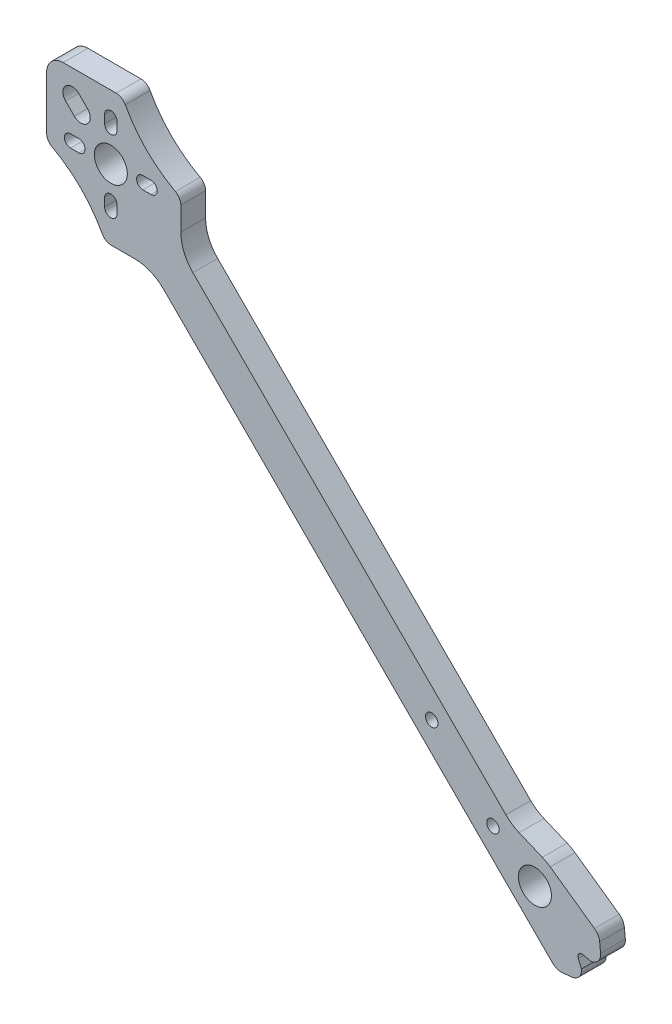
SolidWorks part; units mm, degrees
ref_plane "Alzado" through (0, 0, 0) normal (0, 0, 1) x (1, 0, 0)
ref_plane "Planta" through (0, 0, 0) normal (0, 1, 0) x (1, 0, 0)
ref_plane "Vista lateral" through (0, 0, 0) normal (1, 0, 0) x (0, 0, -1)
sketch "Croquis1" plane through (0, 0, 0) normal (0, 0, 1) x (1, 0, 0)
  line L0 (0, 0) -> (27.8544, 27.8544) construction
  line L1 (0, 0) -> (-42.4264, 42.4264) construction
  line L2 (0, 0) -> (0, 42.4264) construction
  line L3 (15.25, -15.25) -> (-15.25, -15.25) construction
  line L4 (15.25, -15.25) -> (15.25, 15.25) construction
  line L5 (15.25, 15.25) -> (-15.25, 15.25) construction
  line L6 (-15.25, -15.25) -> (-15.25, 15.25) construction
  line L7 (15.25, -15.25) -> (-15.25, 15.25) construction
  line L8 (15.25, 15.25) -> (-15.25, -15.25) construction
  line L9 (0, 42.4264) -> (-20, 42.4264) construction
  line L10 (-42.4264, 42.4264) -> (-38.8909, 45.9619) construction
  line L11 (-38.8909, 45.9619) -> (-31.0962, 38.1673) construction
  line L12 (-20, 42.7635) -> (-20, 80) construction
  line L13 (-42.4264, 42.4264) -> (-45.9619, 38.8909) construction
  line L14 (-45.9619, 38.8909) -> (-38.1673, 31.0962) construction
  line L15 (20, 42.7635) -> (20, 80) construction
  line L16 (38.8909, 45.9619) -> (31.0962, 38.1673) construction
  line L17 (42.4264, 42.4264) -> (38.8909, 45.9619) construction
  line L18 (42.4264, 42.4264) -> (45.9619, 38.8909) construction
  line L19 (-45.9619, -38.8909) -> (-38.1673, -31.0962) construction
  line L20 (0, 0) -> (-15.25, 0) construction
  line L21 (45.9619, 38.8909) -> (38.1673, 31.0962) construction
  line L22 (42.4264, -42.4264) -> (45.9619, -38.8909) construction
  line L23 (42.4264, -42.4264) -> (38.8909, -45.9619) construction
  line L24 (38.8909, -45.9619) -> (31.0962, -38.1673) construction
  line L25 (20, -42.7635) -> (20, -80) construction
  line L26 (-20, -42.7635) -> (-20, -80) construction
  line L27 (-38.8909, -45.9619) -> (-31.0962, -38.1673) construction
  line L28 (-42.4264, -42.4264) -> (-38.8909, -45.9619) construction
  line L29 (-42.4264, -42.4264) -> (-45.9619, -38.8909) construction
  line L30 (45.9619, -38.8909) -> (38.1673, -31.0962) construction
  line L31 (-20, 80) -> (20, 80) construction
  line L32 (0, 80) -> (0, 83) construction
  line L33 (-20, 80) -> (0, 83) construction
  line L34 (0, 83) -> (20, 80) construction
  line L35 (0, -80) -> (0, -83) construction
  line L36 (-20, -80) -> (20, -80) construction
  line L37 (0, -83) -> (20, -80) construction
  line L38 (-20, -80) -> (0, -83) construction
  line L39 (-11, -54) -> (-11, -67.5) construction
  line L41 (-15, -54) -> (-15, -67.5) construction
  line L43 (-13, -54) -> (-13, -67.5) construction
  line L44 (-9, -54) -> (-9, -67.5) construction
  line L45 (-7, -54) -> (-7, -67.5) construction
  line L46 (-5, -54) -> (-5, -67.5) construction
  line L47 (-3, -54) -> (-3, -67.5) construction
  line L48 (-1, -54) -> (-1, -67.5) construction
  line L49 (1, -54) -> (1, -67.5) construction
  line L50 (3, -54) -> (3, -67.5) construction
  line L51 (5, -54) -> (5, -67.5) construction
  line L52 (7, -54) -> (7, -67.5) construction
  line L53 (9, -54) -> (9, -67.5) construction
  line L54 (11, -54) -> (11, -67.5) construction
  line L55 (13, -54) -> (13, -67.5) construction
  line L56 (15, -54) -> (15, -67.5) construction
  line L57 (-11, -35) -> (-11, -48.5) construction
  line L58 (-9, -35) -> (-9, -48.5) construction
  line L59 (-7, -35) -> (-7, -48.5) construction
  line L60 (-5, -35) -> (-5, -48.5) construction
  line L61 (-3, -35) -> (-3, -48.5) construction
  line L62 (-1, -35) -> (-1, -48.5) construction
  line L63 (1, -35) -> (1, -48.5) construction
  line L64 (3, -35) -> (3, -48.5) construction
  line L65 (5, -35) -> (5, -48.5) construction
  line L66 (7, -35) -> (7, -48.5) construction
  line L67 (9, -35) -> (9, -48.5) construction
  line L68 (11, -35) -> (11, -48.5) construction
  line L69 (13, -35) -> (13, -48.5) construction
  line L70 (15, -35) -> (15, -48.5) construction
  line L71 (-15, -35) -> (-15, -48.5) construction
  line L72 (-13, -35) -> (-13, -48.5) construction
  line L73 (-15, 54) -> (-15, 67.5) construction
  line L74 (-13, 35) -> (-13, 48.5) construction
  line L75 (-15, 35) -> (-15, 48.5) construction
  line L76 (15, 35) -> (15, 48.5) construction
  line L77 (13, 35) -> (13, 48.5) construction
  line L78 (11, 35) -> (11, 48.5) construction
  line L79 (9, 35) -> (9, 48.5) construction
  line L80 (7, 35) -> (7, 48.5) construction
  line L81 (5, 35) -> (5, 48.5) construction
  line L82 (3, 35) -> (3, 48.5) construction
  line L83 (1, 35) -> (1, 48.5) construction
  line L84 (-1, 35) -> (-1, 48.5) construction
  line L85 (-3, 35) -> (-3, 48.5) construction
  line L86 (-5, 35) -> (-5, 48.5) construction
  line L87 (-7, 35) -> (-7, 48.5) construction
  line L88 (-9, 35) -> (-9, 48.5) construction
  line L89 (-11, 35) -> (-11, 48.5) construction
  line L90 (15, 54) -> (15, 67.5) construction
  line L91 (13, 54) -> (13, 67.5) construction
  line L92 (11, 54) -> (11, 67.5) construction
  line L93 (9, 54) -> (9, 67.5) construction
  line L94 (7, 54) -> (7, 67.5) construction
  line L95 (5, 54) -> (5, 67.5) construction
  line L96 (3, 54) -> (3, 67.5) construction
  line L97 (1, 54) -> (1, 67.5) construction
  line L98 (-1, 54) -> (-1, 67.5) construction
  line L99 (-3, 54) -> (-3, 67.5) construction
  line L100 (-5, 54) -> (-5, 67.5) construction
  line L101 (-7, 54) -> (-7, 67.5) construction
  line L102 (-9, 54) -> (-9, 67.5) construction
  line L103 (-13, 54) -> (-13, 67.5) construction
  line L104 (-11, 54) -> (-11, 67.5) construction
  line L105 (0, 0) -> (-8.4853, -8.4853) construction
  line L110 (-5.7118, -4.325) -> (-4.3076, -2.2188) construction
  line L111 (-4.325, -5.7118) -> (-2.2188, -4.3076) construction
  line L112 (-4.325, 5.7118) -> (-2.2188, 4.3076) construction
  line L113 (-5.7118, 4.325) -> (-4.3076, 2.2188) construction
  line L114 (5.7118, 4.325) -> (4.3076, 2.2188) construction
  line L115 (4.325, 5.7118) -> (2.2188, 4.3076) construction
  line L116 (4.325, -5.7118) -> (2.2188, -4.3076) construction
  line L117 (5.7118, -4.325) -> (4.3076, -2.2188) construction
  line L123 (-45.9619, 38.8909) -> (-31.0962, 24.0251) construction
  line L124 (-17.1122, 2.2943) -> (-30.516, 23.1236)
  line L125 (-31.8543, 24.7832) -> (-45.9619, 38.8909)
  line L126 (-45.9619, 38.8909) -> (-106.7731, 99.7021)
  line L127 (-31.0962, 24.0251) -> (-24.0251, 31.0962) construction
  line L128 (-38.8909, 45.9619) -> (-24.0251, 31.0962) construction
  line L129 (-2.2943, 17.1122) -> (-23.1236, 30.516)
  line L130 (-24.7832, 31.8543) -> (-38.8909, 45.9619)
  line L131 (-106.7731, 99.7021) -> (-99.7021, 106.7731)
  line L132 (0, 0) -> (-103.2376, 103.2376) construction
  line L135 (-103.2376, 103.2376) -> (-116.6726, 116.6726) construction
  line L168 (-38.8909, 45.9619) -> (-99.7021, 106.7731)
  line L171 (0, 0) -> (-6.364, 6.364) construction
  line L172 (-5.7629, 4.5039) -> (-5.1526, 2.6149)
  line L173 (-7.0557, 0) -> (-12.9076, 0)
  line L174 (-4.5039, 5.7629) -> (-2.6149, 5.1526)
  line L175 (0, 7.0557) -> (0, 12.9076)
  circle A0 centre (-15.25, 15.25) radius 4 construction
  circle A1 centre (-24.0416, 24.0416) radius 1.5 construction
  circle A2 centre (-38.8909, 38.8909) radius 1.5 construction
  arc A3 (-31.0962, 38.1673) -> (-20, 42.7635) centre (-26.5, 42.7635) ccw construction
  arc A4 (31.0962, 38.1673) -> (20, 42.7635) centre (26.5, 42.7635) cw construction
  circle A5 centre (38.8909, 38.8909) radius 1.5 construction
  circle A6 centre (24.0416, 24.0416) radius 1.5 construction
  circle A7 centre (15.25, 15.25) radius 4 construction
  circle A8 centre (15.25, -15.25) radius 4 construction
  circle A9 centre (24.0416, -24.0416) radius 1.5 construction
  circle A10 centre (38.8909, -38.8909) radius 1.5 construction
  arc A11 (31.0962, -38.1673) -> (20, -42.7635) centre (26.5, -42.7635) ccw construction
  circle A12 centre (-15.25, -15.25) radius 4 construction
  circle A13 centre (-24.0416, -24.0416) radius 1.5 construction
  circle A14 centre (-38.8909, -38.8909) radius 1.5 construction
  arc A15 (-31.0962, -38.1673) -> (-20, -42.7635) centre (-26.5, -42.7635) cw construction
  arc A16 (-38.1673, -31.0962) -> (-38.1673, 31.0962) centre (-69.2635, 0) ccw construction
  arc A17 (38.1673, -31.0962) -> (38.1673, 31.0962) centre (69.2635, 0) cw construction
  circle A18 centre (0, 0) radius 1.5 construction
  circle A19 centre (-16, -75) radius 1.5 construction
  circle A20 centre (-16, -30) radius 1.5 construction
  circle A21 centre (-16, 30) radius 1.5 construction
  circle A22 centre (-16, 75) radius 1.5 construction
  circle A23 centre (16, -75) radius 1.5 construction
  circle A24 centre (16, -30) radius 1.5 construction
  circle A25 centre (16, 30) radius 1.5 construction
  circle A26 centre (16, 75) radius 1.5 construction
  arc A27 (-15, -54) -> (-13, -54) centre (-14, -54) cw construction
  arc A28 (-15, -67.5) -> (-13, -67.5) centre (-14, -67.5) ccw construction
  arc A29 (-11, -54) -> (-9, -54) centre (-10, -54) cw construction
  arc A30 (-11, -67.5) -> (-9, -67.5) centre (-10, -67.5) ccw construction
  arc A31 (-7, -54) -> (-5, -54) centre (-6, -54) cw construction
  arc A32 (-7, -67.5) -> (-5, -67.5) centre (-6, -67.5) ccw construction
  arc A33 (-3, -54) -> (-1, -54) centre (-2, -54) cw construction
  arc A34 (-3, -67.5) -> (-1, -67.5) centre (-2, -67.5) ccw construction
  arc A35 (1, -54) -> (3, -54) centre (2, -54) cw construction
  arc A36 (1, -67.5) -> (3, -67.5) centre (2, -67.5) ccw construction
  arc A37 (5, -54) -> (7, -54) centre (6, -54) cw construction
  arc A38 (5, -67.5) -> (7, -67.5) centre (6, -67.5) ccw construction
  arc A39 (9, -54) -> (11, -54) centre (10, -54) cw construction
  arc A40 (9, -67.5) -> (11, -67.5) centre (10, -67.5) ccw construction
  arc A41 (13, -54) -> (15, -54) centre (14, -54) cw construction
  arc A42 (13, -67.5) -> (15, -67.5) centre (14, -67.5) ccw construction
  arc A43 (-11, -35) -> (-9, -35) centre (-10, -35) cw construction
  arc A44 (-11, -48.5) -> (-9, -48.5) centre (-10, -48.5) ccw construction
  arc A45 (-7, -35) -> (-5, -35) centre (-6, -35) cw construction
  arc A46 (-7, -48.5) -> (-5, -48.5) centre (-6, -48.5) ccw construction
  arc A47 (-3, -35) -> (-1, -35) centre (-2, -35) cw construction
  arc A48 (-3, -48.5) -> (-1, -48.5) centre (-2, -48.5) ccw construction
  arc A49 (1, -35) -> (3, -35) centre (2, -35) cw construction
  arc A50 (1, -48.5) -> (3, -48.5) centre (2, -48.5) ccw construction
  arc A51 (5, -35) -> (7, -35) centre (6, -35) cw construction
  arc A52 (5, -48.5) -> (7, -48.5) centre (6, -48.5) ccw construction
  arc A53 (9, -35) -> (11, -35) centre (10, -35) cw construction
  arc A54 (9, -48.5) -> (11, -48.5) centre (10, -48.5) ccw construction
  arc A55 (13, -35) -> (15, -35) centre (14, -35) cw construction
  arc A56 (13, -48.5) -> (15, -48.5) centre (14, -48.5) ccw construction
  arc A57 (-15, -35) -> (-13, -35) centre (-14, -35) cw construction
  arc A58 (-15, -48.5) -> (-13, -48.5) centre (-14, -48.5) ccw construction
  arc A59 (-15, 48.5) -> (-13, 48.5) centre (-14, 48.5) cw construction
  arc A60 (-15, 35) -> (-13, 35) centre (-14, 35) ccw construction
  arc A61 (13, 48.5) -> (15, 48.5) centre (14, 48.5) cw construction
  arc A62 (13, 35) -> (15, 35) centre (14, 35) ccw construction
  arc A63 (9, 48.5) -> (11, 48.5) centre (10, 48.5) cw construction
  arc A64 (9, 35) -> (11, 35) centre (10, 35) ccw construction
  arc A65 (5, 48.5) -> (7, 48.5) centre (6, 48.5) cw construction
  arc A66 (5, 35) -> (7, 35) centre (6, 35) ccw construction
  arc A67 (1, 48.5) -> (3, 48.5) centre (2, 48.5) cw construction
  arc A68 (1, 35) -> (3, 35) centre (2, 35) ccw construction
  arc A69 (-3, 48.5) -> (-1, 48.5) centre (-2, 48.5) cw construction
  arc A70 (-3, 35) -> (-1, 35) centre (-2, 35) ccw construction
  arc A71 (-7, 48.5) -> (-5, 48.5) centre (-6, 48.5) cw construction
  arc A72 (-7, 35) -> (-5, 35) centre (-6, 35) ccw construction
  arc A73 (-11, 48.5) -> (-9, 48.5) centre (-10, 48.5) cw construction
  arc A74 (-11, 35) -> (-9, 35) centre (-10, 35) ccw construction
  arc A75 (13, 67.5) -> (15, 67.5) centre (14, 67.5) cw construction
  arc A76 (13, 54) -> (15, 54) centre (14, 54) ccw construction
  arc A77 (9, 67.5) -> (11, 67.5) centre (10, 67.5) cw construction
  arc A78 (9, 54) -> (11, 54) centre (10, 54) ccw construction
  arc A79 (5, 67.5) -> (7, 67.5) centre (6, 67.5) cw construction
  arc A80 (5, 54) -> (7, 54) centre (6, 54) ccw construction
  arc A81 (1, 67.5) -> (3, 67.5) centre (2, 67.5) cw construction
  arc A82 (1, 54) -> (3, 54) centre (2, 54) ccw construction
  arc A83 (-3, 67.5) -> (-1, 67.5) centre (-2, 67.5) cw construction
  arc A84 (-3, 54) -> (-1, 54) centre (-2, 54) ccw construction
  arc A85 (-7, 67.5) -> (-5, 67.5) centre (-6, 67.5) cw construction
  arc A86 (-7, 54) -> (-5, 54) centre (-6, 54) ccw construction
  arc A87 (-11, 67.5) -> (-9, 67.5) centre (-10, 67.5) cw construction
  arc A88 (-11, 54) -> (-9, 54) centre (-10, 54) ccw construction
  arc A89 (-15, 67.5) -> (-13, 67.5) centre (-14, 67.5) cw construction
  arc A90 (-15, 54) -> (-13, 54) centre (-14, 54) ccw construction
  arc A91 (-4.325, -5.7118) -> (-5.7118, -4.325) centre (-4.8797, -4.8797) cw construction
  arc A92 (-5.7118, 4.325) -> (-4.325, 5.7118) centre (-4.8797, 4.8797) cw construction
  arc A93 (4.325, 5.7118) -> (5.7118, 4.325) centre (4.8797, 4.8797) cw construction
  arc A94 (5.7118, -4.325) -> (4.325, -5.7118) centre (4.8797, -4.8797) cw construction
  circle A95 centre (0, 0) radius 1.5 construction
  arc A96 (2.2188, -4.3076) -> (-2.2188, -4.3076) centre (0, -7.6358) ccw construction
  arc A97 (4.3076, 2.2188) -> (4.3076, -2.2188) centre (7.6358, 0) ccw construction
  arc A98 (-2.2188, 4.3076) -> (2.2188, 4.3076) centre (0, 7.6358) ccw construction
  arc A99 (-4.3076, 2.2188) -> (-4.3076, -2.2188) centre (-7.6358, 0) cw construction
  circle A102 centre (-38.8909, 38.8909) radius 1.5
  circle A103 centre (-24.0416, 24.0416) radius 1.5
  circle A104 centre (-15.25, 15.25) radius 4
  arc A112 (0, 12.9076) -> (-2.2943, 17.1122) centre (-5, 12.9076) ccw
  arc A113 (-12.9076, 0) -> (-17.1122, 2.2943) centre (-12.9076, 5) cw
  arc A114 (-23.1236, 30.516) -> (-24.7832, 31.8543) centre (-17.7121, 38.9253) cw
  arc A115 (-31.8543, 24.7832) -> (-30.516, 23.1236) centre (-38.9253, 17.7121) cw
  arc A143 (-4.5039, 5.7629) -> (-5.7629, 4.5039) centre (-4.8114, 4.8114) ccw
  arc A144 (-2.6149, 5.1526) -> (0, 7.0557) centre (-2, 7.0557) ccw
  arc A145 (-5.1526, 2.6149) -> (-7.0557, 0) centre (-7.0557, 2) cw
  circle A146 centre (-116.6726, 116.6726) radius 88.5 construction
  point P35 (-34.9935, 42.0646)
  point P37 (44.1942, 40.6586)
  point P45 (44.1942, -40.6586)
  point P61 (-34.9935, -42.0646)
  point P305 (0, 0)
  point P308 (-2.8284, 0)
  point P327 (0, 4.3076)
  point P330 (-4.3076, 0)
  point P338 (0, 15.6358)
  point P341 (-15.6358, 0)
  dimension "D2" = 8
  dimension "D4" = 5
  dimension "D8" = 6.5
  dimension "D10" = 3
  dimension "D11" = 3
  dimension "D13" = 4
  dimension "D15" = 3
  dimension "D16" = 3
  dimension "D18" = 45
  dimension "D26" = 1
  dimension "D28" = 4
  dimension "D29" = 19
  dimension "D31" = 177
  dimension "D32" = 9
  dimension "D33" = 5
  dimension "D34" = 10
  dimension "D39" = 1
  dimension "D40" = 2
  dimension "D30" = 5
  dimension "D1" = 30.5
  dimension "D3" = 60
  dimension "D5" = 21
  dimension "D6" = 20
  dimension "D7" = 5
  dimension "D9" = 5
  dimension "D12" = 80
  dimension "D14" = 5
  dimension "D17" = 4
  dimension "D19" = 2
  dimension "D20" = 13.5
  dimension "D21" = 7.5
  dimension "D22" = 5
  dimension "D25" = 12
  dimension "D35" = 165
  dimension "D23" = 8
  dimension "D24" = 2
  dimension "D27" = 4
extrude "Saliente-Extruir1" add sketch "Croquis1" along normal blind 6
sketch "Croquis4" plane through (0, 0, 6) normal (0, 0, 1) x (1, 0, 0)
  line L0 (-106.7731, 99.7021) -> (-118.0868, 99.7021)
  line L1 (-118.0868, 99.7021) -> (-132.229, 113.8442)
  line L2 (-116.6726, 116.6726) -> (-132.229, 132.229) construction
  line L3 (-132.229, 113.8442) -> (-132.229, 132.229)
  line L4 (-99.7021, 106.7731) -> (-99.7021, 118.0868)
  line L5 (-99.7021, 118.0868) -> (-113.8442, 132.229)
  line L6 (-113.8442, 132.229) -> (-132.229, 132.229)
  line L7 (-106.7731, 99.7021) -> (-99.7021, 106.7731)
  circle A0 centre (-116.6726, 116.6726) radius 4
  dimension "D1" = 22
  dimension "D2" = 13
extrude "Saliente-Extruir3" add sketch "Croquis4" against normal up to vertex (6 mm away)
sketch "Croquis5" plane through (0, 0, 6) normal (0, 0, 1) x (1, 0, 0)
  line L0 (-116.6726, 116.6726) -> (-132.229, 132.229) construction
  line L2 (-127.6328, 124.4508) -> (-125.5115, 122.3295)
  line L4 (-122.3295, 125.5115) -> (-124.4508, 127.6328)
  line L6 (-119.501, 119.501) -> (-122.3295, 122.3295) construction
  line L7 (-116.6726, 116.6726) -> (-82.0244, 116.6726) construction
  line L8 (-118.1726, 108.9226) -> (-118.1726, 106.9226)
  line L9 (-108.9226, 115.1726) -> (-106.9226, 115.1726)
  line L11 (-108.9226, 118.1726) -> (-106.9226, 118.1726)
  line L13 (-115.1726, 108.9226) -> (-115.1726, 106.9226)
  line L14 (-124.4226, 118.1726) -> (-126.4226, 118.1726)
  line L15 (-124.4226, 115.1726) -> (-126.4226, 115.1726)
  line L16 (-115.1726, 124.4226) -> (-115.1726, 126.4226)
  line L17 (-118.1726, 124.4226) -> (-118.1726, 126.4226)
  arc A0 (-127.6328, 124.4508) -> (-124.4508, 127.6328) centre (-126.0418, 126.0418) cw
  arc A1 (-125.5115, 122.3295) -> (-122.3295, 125.5115) centre (-123.9205, 123.9205) ccw
  circle A2 centre (-116.6726, 116.6726) radius 4 construction
  arc A3 (-106.9226, 118.1726) -> (-106.9226, 115.1726) centre (-106.9226, 116.6726) cw
  arc A4 (-108.9226, 115.1726) -> (-108.9226, 118.1726) centre (-108.9226, 116.6726) cw
  arc A5 (-115.1726, 106.9226) -> (-118.1726, 106.9226) centre (-116.6726, 106.9226) cw
  arc A6 (-118.1726, 108.9226) -> (-115.1726, 108.9226) centre (-116.6726, 108.9226) cw
  arc A7 (-126.4226, 115.1726) -> (-126.4226, 118.1726) centre (-126.4226, 116.6726) cw
  arc A8 (-124.4226, 118.1726) -> (-124.4226, 115.1726) centre (-124.4226, 116.6726) cw
  arc A9 (-118.1726, 126.4226) -> (-115.1726, 126.4226) centre (-116.6726, 126.4226) cw
  arc A10 (-115.1726, 124.4226) -> (-118.1726, 124.4226) centre (-116.6726, 124.4226) cw
  point P23 (-110.4226, 116.6726)
  point P43 (-116.6726, 116.6726)
  dimension "D1" = 3
  dimension "D2" = 4
  dimension "D3" = 4.5
  dimension "D4" = 2.25
  dimension "D5" = 3
  dimension "D6" = 1.5
  dimension "D7" = 2
  dimension "D8" = 6.25
extrude "Cortar-Extruir1" cut sketch "Croquis5" against normal up to vertex (6 mm away)
fillet "Redondeo3" radius 4 1 edges at (-132.229, 132.229, 3)
sketch "Croquis7" plane through (0, 0, 6) normal (0, 0, 1) x (1, 0, 0)
  line L0 (-132.229, 113.8442) -> (-118.0868, 99.7021)
  line L3 (-116.6726, 116.6726) -> (-82.0244, 82.0244) construction
  line L4 (-113.8442, 132.229) -> (-99.7021, 118.0868)
  arc A0 (-132.229, 113.8442) -> (-118.0868, 99.7021) centre (-145.1579, 86.7731) cw
  arc A1 (-113.8442, 132.229) -> (-99.7021, 118.0868) centre (-86.7731, 145.1579) ccw
  dimension "D1" = 30
extrude "Cortar-Extruir2" cut sketch "Croquis7" against normal up to vertex (6 mm away)
fillet "Redondeo4" radius 2.5 4 edges at (-113.8442, 132.229, 3) (-99.7021, 118.0868, 3) (-118.0868, 99.7021, 3) (-132.229, 113.8442, 3)
fillet "Redondeo6" radius 10 2 edges at (-99.7021, 106.7731, 3) (-106.7731, 99.7021, 3)
sketch "Croquis9" plane through (0, 0, 6) normal (0, 0, 1) x (1, 0, 0)
  line L0 (-31.8543, 24.7832) -> (-23.0476, 15.9766)
  line L1 (-103.8442, 96.7731) -> (-31.8543, 24.7832) construction
  line L2 (-24.7832, 31.8543) -> (-15.9766, 23.0476)
  line L3 (-15.9766, 23.0476) -> (-23.0524, 15.9718)
  line L52 (-23.1236, 30.516) -> (-2.2943, 17.1122)
  line L53 (0, 12.9076) -> (0, 7.0557)
  line L54 (-2.6149, 5.1526) -> (-4.5039, 5.7629)
  line L55 (-5.7629, 4.5039) -> (-5.1526, 2.6149)
  line L56 (-7.0557, 0) -> (-12.9076, 0)
  line L57 (-17.1122, 2.2943) -> (-30.516, 23.1236)
  line L58 (-23.1236, 30.516) -> (-2.2943, 17.1122)
  line L59 (0, 12.9076) -> (0, 7.0557)
  line L60 (-2.6149, 5.1526) -> (-4.5039, 5.7629)
  line L61 (-5.7629, 4.5039) -> (-5.1526, 2.6149)
  line L62 (-7.0557, 0) -> (-12.9076, 0)
  line L63 (-17.1122, 2.2943) -> (-30.516, 23.1236)
  arc A58 (-24.7832, 31.8543) -> (-23.1236, 30.516) centre (-17.7121, 38.9253) ccw
  arc A59 (0, 12.9076) -> (-2.2943, 17.1122) centre (-5, 12.9076) ccw
  arc A60 (-2.6149, 5.1526) -> (0, 7.0557) centre (-2, 7.0557) ccw
  arc A61 (-4.5039, 5.7629) -> (-5.7629, 4.5039) centre (-4.8114, 4.8114) ccw
  arc A62 (-7.0557, 0) -> (-5.1526, 2.6149) centre (-7.0557, 2) ccw
  arc A63 (-17.1122, 2.2943) -> (-12.9076, 0) centre (-12.9076, 5) ccw
  arc A64 (-30.516, 23.1236) -> (-31.8543, 24.7832) centre (-38.9253, 17.7121) ccw
  arc A65 (-24.7832, 31.8543) -> (-23.1236, 30.516) centre (-17.7121, 38.9253) ccw
  arc A66 (0, 12.9076) -> (-2.2943, 17.1122) centre (-5, 12.9076) ccw
  arc A67 (-2.6149, 5.1526) -> (0, 7.0557) centre (-2, 7.0557) ccw
  arc A68 (-4.5039, 5.7629) -> (-5.7629, 4.5039) centre (-4.8114, 4.8114) ccw
  arc A69 (-7.0557, 0) -> (-5.1526, 2.6149) centre (-7.0557, 2) ccw
  arc A70 (-17.1122, 2.2943) -> (-12.9076, 0) centre (-12.9076, 5) ccw
  arc A71 (-30.516, 23.1236) -> (-31.8543, 24.7832) centre (-38.9253, 17.7121) ccw
  dimension "D1" = 0
extrude "Cortar-Extruir3" cut sketch "Croquis9" against normal up to vertex (6 mm away)
sketch "Croquis14" plane through (0, 0, 6) normal (0, 0, 1) x (1, 0, 0)
  line L0 (2.7929, 2.655) -> (1.2343, 18.5775)
  line L1 (2.7929, 2.655) -> (23.1079, 4.6436)
  line L3 (-103.8442, 96.7731) -> (-23.0476, 15.9766) construction
  circle A1 centre (-13.8811, 16.5029) radius 4
  circle A3 centre (2.7929, 2.655) radius 3.5
  arc A4 (0.625, 18.2768) -> (1.8832, 18.4158) centre (1.1691, 19.1158) ccw construction
  arc A5 (-32.6308, 25.5597) -> (-30.4347, -14.4153) centre (-53.844, 4.3465) cw
  point P10 (1.2789, 18.1219)
sketch "Croquis15" plane through (0, 0, 6) normal (0, 0, 1) x (1, 0, 0)
  line L0 (2.7929, 2.655) -> (1.3029, 17.8763) construction
  line L1 (2.7929, 2.655) -> (-21.5107, 0.2759) construction
  line L2 (-15.9766, 23.0476) -> (1.3029, 17.8763) construction
  line L3 (-23.0476, 15.9766) -> (-21.5107, 0.2759) construction
  line L4 (-15.9766, 23.0476) -> (-23.0476, 15.9766)
  line L5 (-2.5899, 4.7555) -> (-3.3814, 6.576) construction
  line L6 (-2.251, 7.9517) -> (-0.3115, 7.5283) construction
  line L7 (4.8934, 8.0378) -> (6.714, 8.8293) construction
  line L8 (8.0897, 7.6989) -> (7.6662, 5.7595) construction
  line L9 (8.1757, 0.5545) -> (8.9672, -1.266) construction
  line L10 (7.8369, -2.6417) -> (5.8974, -2.2183) construction
  line L11 (0.6924, -2.7278) -> (-1.1281, -3.5193) construction
  line L12 (-2.5038, -2.3889) -> (-2.0804, -0.4495) construction
  line L13 (7.1127, 7.9122) -> (-1.5268, -2.6022) construction
  line L14 (-0.3115, 7.5283) -> (-2.251, 7.9517)
  line L15 (-3.3814, 6.576) -> (-2.5899, 4.7555)
  line L16 (-2.5899, 4.7555) -> (-2.3351, 2.153) construction
  line L17 (-2.3351, 2.153) -> (-5.1924, 4.5008) construction
  line L18 (-5.1924, 4.5008) -> (-2.5899, 4.7555) construction
  line L19 (-5.1924, 4.5008) -> (-4.9376, 1.8983) construction
  line L20 (-4.9376, 1.8983) -> (-21.5107, 0.2759) construction
  line L21 (-3.2369, 7.6096) -> (2.7929, 2.655) construction
  line L22 (-11.0599, 23.0476) -> (1.6767, 14.0578) construction
  line L23 (-15.9766, 23.0476) -> (-19.5121, 26.5832)
  line L24 (-15.9766, 23.0476) -> (-96.7731, 103.8442) construction
  line L27 (-19.5121, 26.5832) -> (1.3029, 17.8763) construction
  line L29 (-19.5121, 26.5832) -> (-11.0599, 23.0476)
  line L30 (-11.0599, 23.0476) -> (1.6767, 14.0578)
  line L31 (1.6767, 14.0578) -> (2.0362, 10.3856)
  line L35 (-8.6099, 1.5388) -> (-4.9376, 1.8983)
  line L36 (-23.0476, 15.9766) -> (-8.6099, 1.5388)
  line L37 (-103.8442, 96.7731) -> (-23.0476, 15.9766) construction
  circle A0 centre (-13.8811, 16.5029) radius 4
  arc A1 (-3.3814, 6.576) -> (-2.251, 7.9517) centre (-2.4643, 6.9748) cw construction
  arc A2 (6.714, 8.8293) -> (8.0897, 7.6989) centre (7.1127, 7.9122) cw construction
  arc A3 (8.9672, -1.266) -> (7.8369, -2.6417) centre (8.0502, -1.6647) cw construction
  arc A4 (-1.1281, -3.5193) -> (-2.5038, -2.3889) centre (-1.5268, -2.6022) cw construction
  arc A5 (-0.3115, 7.5283) -> (4.8934, 8.0378) centre (1.5834, 15.0108) ccw construction
  arc A6 (7.6662, 5.7595) -> (8.1757, 0.5545) centre (15.1488, 3.8645) ccw construction
  arc A7 (5.8974, -2.2183) -> (0.6924, -2.7278) centre (4.0024, -9.7008) ccw construction
  arc A8 (-2.0804, -0.4495) -> (-2.5899, 4.7555) centre (-9.5629, 1.4455) ccw construction
  circle A10 centre (2.7929, 2.655) radius 1.5 construction
  arc A11 (-2.251, 7.9517) -> (-3.3814, 6.576) centre (-2.4643, 6.9748) ccw
  arc A12 (-2.5899, 4.7555) -> (-4.9376, 1.8983) centre (-5.1924, 4.5008) cw
  arc A13 (-0.3115, 7.5283) -> (2.0362, 10.3856) centre (-0.5663, 10.1308) ccw
  point P50 (-8.2406, 23.423)
  point P51 (0, 0)
  point P54 (-11.0599, 23.0476)
  dimension "D1" = 8
  dimension "D2" = 45
  dimension "D3" = 5
extrude "Saliente-Extruir4" add sketch "Croquis15" against normal up to vertex (6 mm away)
fillet "Redondeo12" radius 10 2 edges at (-19.5121, 26.5832, 3) (-11.0599, 23.0476, 3)
fillet "Redondeo13" radius 3 2 edges at (-8.6099, 1.5388, 3) (1.6767, 14.0578, 3)
